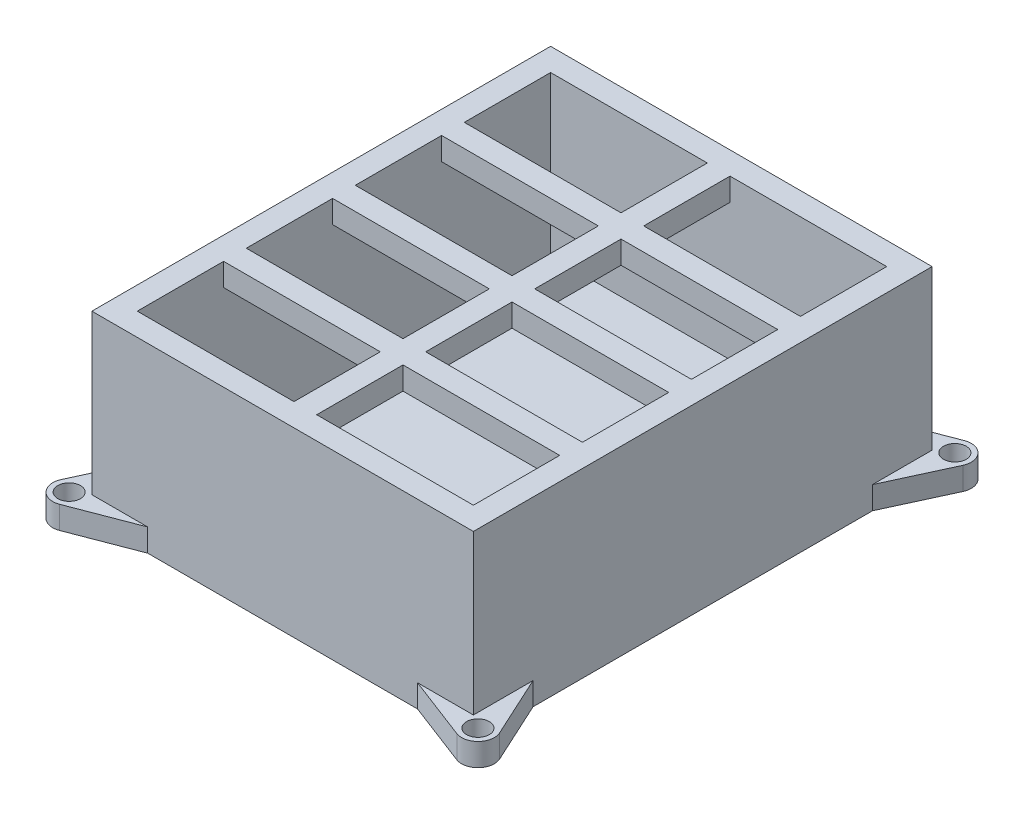
SolidWorks part; units mm, degrees
ref_plane "Front Plane" through (0, 0, 0) normal (0, 0, 1) x (1, 0, 0)
ref_plane "Top Plane" through (0, 0, 0) normal (0, 1, 0) x (1, 0, 0)
ref_plane "Right Plane" through (0, 0, 0) normal (1, 0, 0) x (0, 0, -1)
sketch "Sketch1" plane through (0, 0, 0) normal (0, 1, 0) x (1, 0, 0)
  line L0 (0, 0) -> (0, 10.1) construction
  line L1 (-8.4, -10.1) -> (8.4, -10.1)
  line L2 (-8.4, -10.1) -> (-8.4, 10.1)
  line L3 (-8.4, 10.1) -> (8.4, 10.1)
  line L4 (8.4, -10.1) -> (8.4, 10.1)
  line L5 (-8.4, -10.1) -> (8.4, 10.1) construction
  line L6 (-8.4, 10.1) -> (8.4, -10.1) construction
  line L7 (0, 0) -> (8.4, 0) construction
  line L9 (-7.4, -5.3) -> (-0.5, -5.3)
  line L10 (-7.4, -5.3) -> (-7.4, -9.1)
  line L11 (-7.4, -9.1) -> (-0.5, -9.1)
  line L12 (-0.5, -5.3) -> (-0.5, -9.1)
  line L16 (7.4, -9.1) -> (0.5, -9.1)
  line L17 (0.5, -5.3) -> (0.5, -9.1)
  line L18 (7.4, -5.3) -> (0.5, -5.3)
  line L19 (7.4, -5.3) -> (7.4, -9.1)
  line L20 (-7.4, -0.5) -> (-7.4, -4.3)
  line L21 (-7.4, -0.5) -> (-0.5, -0.5)
  line L22 (-0.5, -0.5) -> (-0.5, -4.3)
  line L23 (-7.4, -4.3) -> (-0.5, -4.3)
  line L24 (7.4, -4.3) -> (0.5, -4.3)
  line L25 (0.5, -0.5) -> (0.5, -4.3)
  line L26 (7.4, -0.5) -> (0.5, -0.5)
  line L27 (7.4, -0.5) -> (7.4, -4.3)
  line L44 (7.4, 0.5) -> (7.4, 4.3)
  line L45 (7.4, 0.5) -> (0.5, 0.5)
  line L46 (0.5, 0.5) -> (0.5, 4.3)
  line L47 (7.4, 4.3) -> (0.5, 4.3)
  line L48 (7.4, 5.3) -> (7.4, 9.1)
  line L49 (7.4, 5.3) -> (0.5, 5.3)
  line L50 (0.5, 5.3) -> (0.5, 9.1)
  line L51 (7.4, 9.1) -> (0.5, 9.1)
  line L52 (-7.4, 9.1) -> (-0.5, 9.1)
  line L53 (-0.5, 5.3) -> (-0.5, 9.1)
  line L54 (-7.4, 5.3) -> (-0.5, 5.3)
  line L55 (-7.4, 5.3) -> (-7.4, 9.1)
  line L56 (-7.4, 0.5) -> (-0.5, 0.5)
  line L57 (-0.5, 0.5) -> (-0.5, 4.3)
  line L58 (-7.4, 4.3) -> (-0.5, 4.3)
  line L59 (-7.4, 0.5) -> (-7.4, 4.3)
  point P0 (0, 0)
  point P43 (-3.95, 9.1)
  dimension "D1" = 6.9
  dimension "D2" = 3.8
  dimension "D4" = 1
  dimension "D5" = 1
  dimension "D6" = 1
  dimension "D7" = 1
  dimension "D8" = 1
  dimension "D3" = 2
extrude "Boss-Extrude1" add sketch "Sketch1" along normal blind 1 contours L1 L4 L3 L2 L51 L48 L49 L50 L47 L44 L45 L46 L23 L20 L21 L22 L9 L12 L11 L10 L18 L19 L16 L17 L26 L27 L24 L25 L54 L55 L52 L53 L56 L59 L58 L57 | L59 L56 L57 L58 | L55 L54 L53 L52 | L48 L51 L50 L49 | L44 L47 L46 L45 | L27 L26 L25 L24 | L20 L23 L22 L21 | L12 L9 L10 L11 | L19 L18 L17 L16
ref_plane "Plane1" through (0, 7, 0) normal (0, 1, 0) x (1, 0, 0)
sketch "Sketch2" plane through (0, 7, 0) normal (0, 1, 0) x (1, 0, 0)
  line L0 (-7.4, -5.3) -> (-7.4, -9.1) construction
  line L1 (-7.4, -5.3) -> (-0.5, -5.3) construction
  line L2 (-0.5, -5.3) -> (-0.5, -9.1) construction
  line L3 (-7.4, -9.1) -> (-0.5, -9.1) construction
  line L4 (-8.4, -10.1) -> (8.4, -10.1)
  line L6 (-8.4, -10.1) -> (8.4, -10.1)
  line L12 (7.4, -9.1) -> (0.5, -9.1) construction
  line L13 (7.4, -5.3) -> (7.4, -9.1) construction
  line L14 (0.5, -5.3) -> (0.5, -9.1) construction
  line L15 (7.4, -5.3) -> (0.5, -5.3) construction
  line L16 (7.4, -0.5) -> (7.4, -4.3) construction
  line L17 (7.4, -0.5) -> (0.5, -0.5) construction
  line L18 (7.4, -4.3) -> (0.5, -4.3) construction
  line L19 (0.5, -0.5) -> (0.5, -4.3) construction
  line L20 (-0.5, -0.5) -> (-0.5, -4.3) construction
  line L21 (-7.4, -4.3) -> (-0.5, -4.3) construction
  line L22 (-7.4, -0.5) -> (-7.4, -4.3) construction
  line L23 (-7.4, -0.5) -> (-0.5, -0.5) construction
  line L24 (-0.5, 0.5) -> (-0.5, 4.3) construction
  line L25 (-7.4, 4.3) -> (-0.5, 4.3) construction
  line L26 (-7.4, 0.5) -> (-7.4, 4.3) construction
  line L27 (-7.4, 0.5) -> (-0.5, 0.5) construction
  line L28 (7.4, 0.5) -> (7.4, 4.3) construction
  line L29 (7.4, 0.5) -> (0.5, 0.5) construction
  line L30 (0.5, 0.5) -> (0.5, 4.3) construction
  line L31 (7.4, 4.3) -> (0.5, 4.3) construction
  line L32 (7.4, 5.3) -> (7.4, 9.1) construction
  line L33 (7.4, 9.1) -> (0.5, 9.1) construction
  line L34 (7.4, 5.3) -> (0.5, 5.3) construction
  line L35 (0.5, 5.3) -> (0.5, 9.1) construction
  line L36 (-0.5, 5.3) -> (-0.5, 9.1) construction
  line L37 (-7.4, 5.3) -> (-0.5, 5.3) construction
  line L38 (-7.4, 5.3) -> (-7.4, 9.1) construction
  line L39 (-7.4, 9.1) -> (-0.5, 9.1) construction
  line L40 (-7.4, -5.3) -> (-7.4, -9.1)
  line L41 (-7.4, -5.3) -> (-0.5, -5.3)
  line L42 (-0.5, -5.3) -> (-0.5, -9.1)
  line L43 (-7.4, -9.1) -> (-0.5, -9.1)
  line L44 (7.4, -9.1) -> (0.5, -9.1)
  line L45 (7.4, -5.3) -> (7.4, -9.1)
  line L46 (0.5, -5.3) -> (0.5, -9.1)
  line L47 (7.4, -5.3) -> (0.5, -5.3)
  line L48 (7.4, -0.5) -> (7.4, -4.3)
  line L49 (7.4, -0.5) -> (0.5, -0.5)
  line L50 (7.4, -4.3) -> (0.5, -4.3)
  line L51 (0.5, -0.5) -> (0.5, -4.3)
  line L52 (-0.5, -0.5) -> (-0.5, -4.3)
  line L53 (-7.4, -4.3) -> (-0.5, -4.3)
  line L54 (-7.4, -0.5) -> (-7.4, -4.3)
  line L55 (-7.4, -0.5) -> (-0.5, -0.5)
  line L56 (-0.5, 0.5) -> (-0.5, 4.3)
  line L57 (-7.4, 4.3) -> (-0.5, 4.3)
  line L58 (-7.4, 0.5) -> (-7.4, 4.3)
  line L59 (-7.4, 0.5) -> (-0.5, 0.5)
  line L60 (7.4, 0.5) -> (7.4, 4.3)
  line L61 (7.4, 0.5) -> (0.5, 0.5)
  line L62 (0.5, 0.5) -> (0.5, 4.3)
  line L63 (7.4, 4.3) -> (0.5, 4.3)
  line L64 (7.4, 5.3) -> (7.4, 9.1)
  line L65 (7.4, 9.1) -> (0.5, 9.1)
  line L66 (7.4, 5.3) -> (0.5, 5.3)
  line L67 (0.5, 5.3) -> (0.5, 9.1)
  line L68 (-0.5, 5.3) -> (-0.5, 9.1)
  line L69 (-7.4, 5.3) -> (-0.5, 5.3)
  line L70 (-7.4, 5.3) -> (-7.4, 9.1)
  line L71 (-7.4, 9.1) -> (-0.5, 9.1)
  line L76 (8.4, -10.1) -> (8.4, 10.1)
  line L78 (8.4, -10.1) -> (8.4, 10.1)
  line L80 (8.4, 10.1) -> (-8.4, 10.1)
  line L81 (8.4, 10.1) -> (-8.4, 10.1)
  line L82 (-8.4, 10.1) -> (-8.4, -10.1)
  line L83 (-8.4, 10.1) -> (-8.4, -10.1)
  dimension "D1" = 0
extrude "Boss-Extrude2" add sketch "Sketch2" along normal blind 1 separate body
sketch "Sketch4" plane through (0, 1, 0) normal (0, 1, 0) x (1, 0, 0)
  line L4 (-8.4, -10.1) -> (8.4, -10.1)
  line L6 (-8.4, -10.1) -> (8.4, -10.1)
  line L24 (8.4, -10.1) -> (8.4, 10.1)
  line L26 (8.4, -10.1) -> (8.4, 10.1)
  line L40 (8.4, 10.1) -> (-8.4, 10.1)
  line L41 (8.4, 10.1) -> (-8.4, 10.1)
  line L42 (-8.4, 10.1) -> (-8.4, -10.1)
  line L43 (-8.4, 10.1) -> (-8.4, -10.1)
  line L48 (-7.4, 9.1) -> (-7.4, -9.1)
  line L49 (-7.4, -9.1) -> (7.4, -9.1)
  line L50 (7.4, -9.1) -> (7.4, 9.1)
  line L51 (7.4, 9.1) -> (-7.4, 9.1)
  line L52 (-7.4, 9.1) -> (-7.4, -9.1)
  line L53 (-7.4, -9.1) -> (7.4, -9.1)
  line L54 (7.4, -9.1) -> (7.4, 9.1)
  line L55 (7.4, 9.1) -> (-7.4, 9.1)
  dimension "D1" = 0
  dimension "D2" = 1
extrude "Boss-Extrude3" add sketch "Sketch4" along normal up to surface (6 mm away) up to face at (3.95, 7, -7.2)
sketch "Sketch5" plane through (0, 0, 0) normal (0, -1, 0) x (1, 0, 0)
  line L0 (0, 0) -> (0, 5.3631) construction
  line L1 (9.655, 10.1983) -> (8.4, 7.4735)
  line L3 (8.742, 11.1734) -> (5.9406, 10.1)
  line L5 (-9, -10.5) -> (9, -10.5) construction
  line L6 (-9, -10.5) -> (-9, 10.5) construction
  line L17 (-9, 10.5) -> (9, 10.5) construction
  line L18 (9, -10.5) -> (9, 10.5) construction
  line L19 (-9, -10.5) -> (9, 10.5) construction
  line L20 (-9, 10.5) -> (9, -10.5) construction
  line L25 (0, 0) -> (3.0583, 0) construction
  line L30 (-9.655, 10.1983) -> (-8.4, 7.4735)
  line L31 (-8.4, 10.1) -> (-8.4, -10.1) construction
  line L32 (-8.742, 11.1734) -> (-5.9406, 10.1)
  line L33 (-8.4, 10.1) -> (8.4, 10.1) construction
  line L34 (-9.655, -10.1983) -> (-8.4, -7.4735)
  line L35 (-8.742, -11.1734) -> (-5.9406, -10.1)
  line L36 (9.655, -10.1983) -> (8.4, -7.4735)
  line L37 (8.742, -11.1734) -> (5.9406, -10.1)
  line L38 (-5.9406, 10.1) -> (-8.4, 10.1)
  line L39 (-8.4, -7.4735) -> (-8.4, -10.1)
  line L40 (8.4, 7.4735) -> (8.4, 10.1)
  line L41 (5.9406, -10.1) -> (8.4, -10.1)
  line L42 (8.4, 10.1) -> (-8.4, 10.1)
  line L43 (-8.4, 10.1) -> (-8.4, -10.1)
  line L44 (-8.4, -10.1) -> (8.4, -10.1)
  line L45 (8.4, -10.1) -> (8.4, 10.1)
  line L46 (8.4, 10.1) -> (5.9406, 10.1)
  line L47 (-8.4, 10.1) -> (-8.4, 7.4735)
  line L48 (-8.4, -10.1) -> (-5.9406, -10.1)
  line L49 (8.4, -10.1) -> (8.4, -7.4735)
  circle A8 centre (-9, 10.5) radius 0.5
  circle A9 centre (9, 10.5) radius 0.5
  circle A10 centre (9, -10.5) radius 0.5
  circle A11 centre (-9, -10.5) radius 0.5
  arc A12 (-8.5307, 9.9525) -> (-8.4, 10.1) centre (-9, 10.5) ccw
  arc A13 (8.742, 11.1734) -> (9.655, 10.1983) centre (9, 10.5) cw
  arc A14 (-8.5307, -9.9525) -> (-8.4, -10.1) centre (-9, -10.5) cw
  arc A15 (8.742, -11.1734) -> (9.655, -10.1983) centre (9, -10.5) ccw
  arc A16 (-8.742, 11.1734) -> (-9.655, 10.1983) centre (-9, 10.5) ccw
  arc A17 (8.5307, 9.9525) -> (8.4, 10.1) centre (9, 10.5) cw
  arc A18 (8.5307, -9.9525) -> (8.4, -10.1) centre (9, -10.5) ccw
  arc A19 (-8.742, -11.1734) -> (-9.655, -10.1983) centre (-9, -10.5) cw
  point P0 (0, 0)
  dimension "D1" = 1
  dimension "D2" = 18
  dimension "D3" = 21
  dimension "D4" = 3
  dimension "D5" = 0
extrude "Boss-Extrude4" add sketch "Sketch5" against normal blind 1
